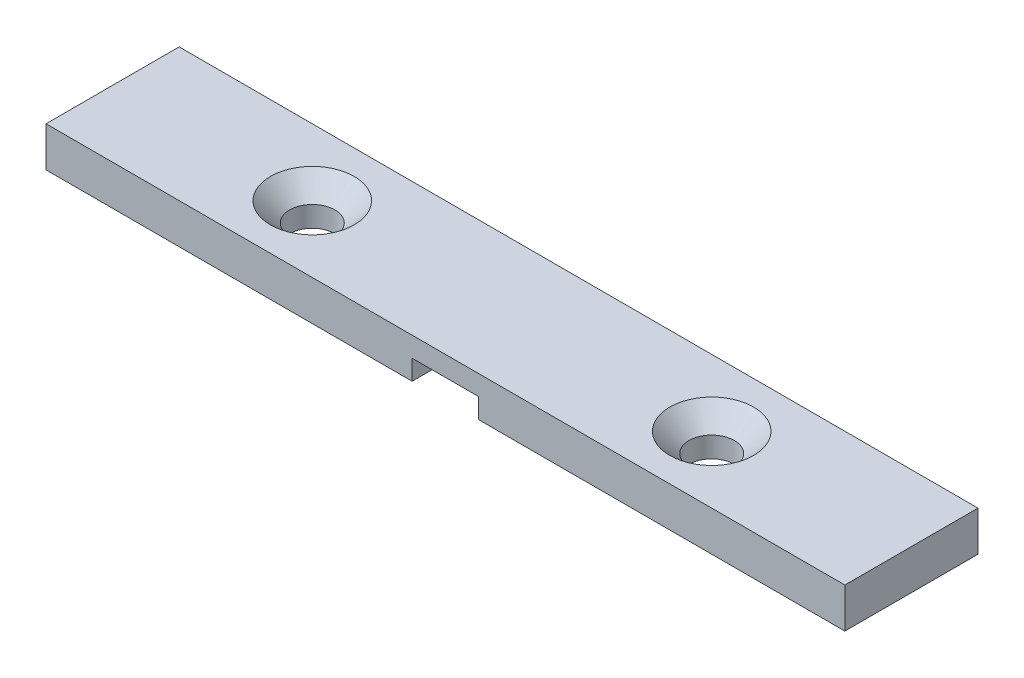
SolidWorks part; units mm, degrees
ref_plane "Front Plane" through (0, 0, 0) normal (0, 0, 1) x (1, 0, 0)
ref_plane "Top Plane" through (0, 0, 0) normal (0, 1, 0) x (1, 0, 0)
ref_plane "Right Plane" through (0, 0, 0) normal (1, 0, 0) x (0, 0, -1)
sketch "Sketch1" plane through (0, 0, 0) normal (0, 1, 0) x (1, 0, 0)
  line L1 (-30, 5) -> (30, 5)
  line L2 (-30, 5) -> (-30, -5)
  line L3 (-30, -5) -> (30, -5)
  line L4 (30, 5) -> (30, -5)
  line L5 (-30, 5) -> (30, -5) construction
  line L6 (-30, -5) -> (30, 5) construction
  point P0 (0, 0)
  dimension "D1" = 60
  dimension "D2" = 10
extrude "Boss-Extrude1" add sketch "Sketch1" along normal blind 3
sketch "Sketch2" plane through (0, 3, 0) normal (0, 1, 0) x (1, 0, 0)
  line L0 (-15, 0) -> (15, 0) construction
  dimension "D1" = 30
  dimension "D2" = 15
hole_wizard "CSK for M3 Countersunk Flat Head Screw1" positions "3DSketch1" profile "Sketch3" countersink size "M3" standard "DIN"
sketch3d "3DSketch1"
  point P0 (-15, 3, 0)
  point P3 (15, 3, 0)
sketch "Sketch3" plane through (-15, 3, 0) normal (1, 0, 0) x (0, 0, 1)
  line L0 (0, 0) -> (0, 8.5215)
  line L1 (0, 8.5215) -> (1.7, 7.5)
  line L2 (1.7, 7.5) -> (1.7, 1.45)
  line L3 (1.7, 1.45) -> (3.15, 0)
  line L5 (3.15, 0) -> (0, 0)
  line L6 (-1.7, 1.45) -> (-3.15, 0) construction
  line L10 (0, 8.5215) -> (-1.7, 7.5) construction
  line L11 (0, -6.35) -> (0, 107.95) construction
  dimension "Hole Dia." = 3.4
  dimension "Hole Depth" = 7.5
  dimension "Near C'Sink Dia." = 6.3
  dimension "Near C'Sink Angle" = 90
  dimension "Drill Angle" = 118
sketch "Sketch4" plane through (0, 0, 5) normal (0, 0, 1) x (1, 0, 0)
  line L0 (-30, 0) -> (30, 0) construction
  line L1 (-2.5, 0) -> (2.5, 0)
  line L2 (-2.5, 0) -> (-2.5, 1.5)
  line L3 (-2.5, 1.5) -> (2.5, 1.5)
  line L4 (2.5, 0) -> (2.5, 1.5)
  dimension "D1" = 1.5
  dimension "D2" = 5
  dimension "D3" = 2.5
extrude "Cut-Extrude1" cut sketch "Sketch4" against normal blind 8.5
